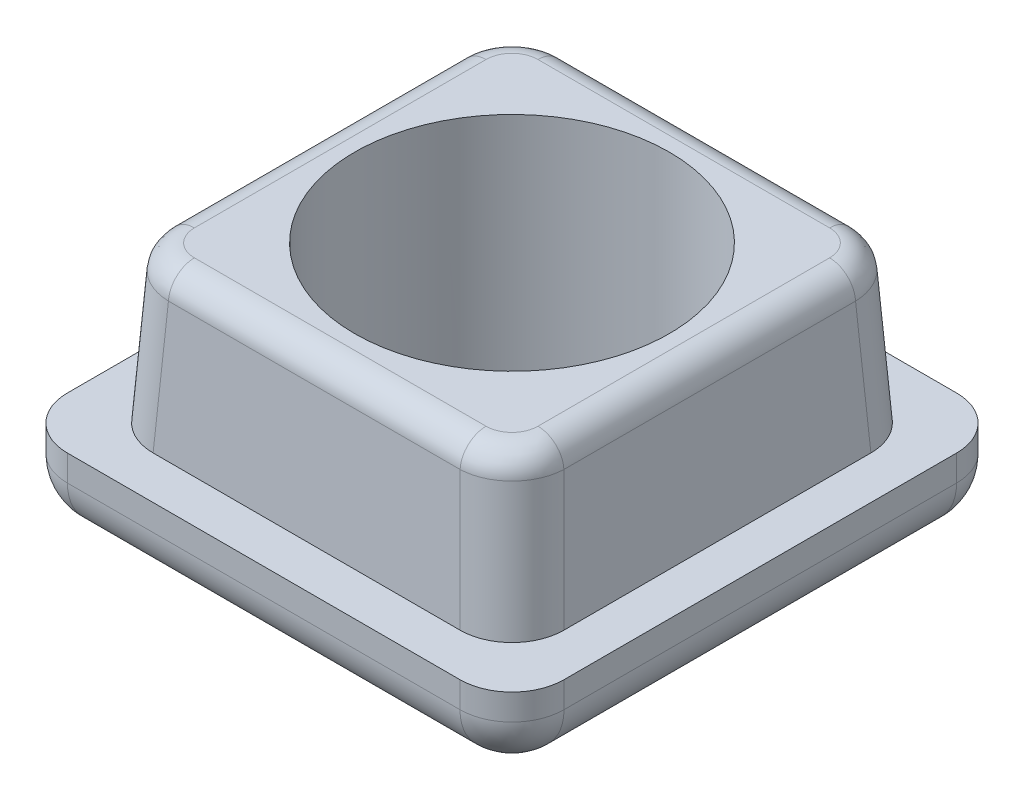
SolidWorks part; units mm, degrees
ref_plane "Front Plane" through (0, 0, 0) normal (0, 0, 1) x (1, 0, 0)
ref_plane "Top Plane" through (0, 0, 0) normal (0, 1, 0) x (1, 0, 0)
ref_plane "Right Plane" through (0, 0, 0) normal (1, 0, 0) x (0, 0, -1)
sketch "Sketch1" plane through (0, 0, 0) normal (0, 1, 0) x (1, 0, 0)
  line L1 (0, 0) -> (19.1, 0)
  line L2 (0, 0) -> (0, 19.1)
  line L3 (0, 19.1) -> (19.1, 19.1)
  line L4 (19.1, 0) -> (19.1, 19.1)
  dimension "D1" = 19.1
extrude "Boss-Extrude1" add sketch "Sketch1" along normal blind 3
sketch "Sketch2" plane through (0, 3, 0) normal (0, 1, 0) x (1, 0, 0)
  line L8 (1.65, 1.65) -> (17.45, 1.65)
  line L9 (17.45, 1.65) -> (17.45, 17.45)
  line L10 (1.65, 17.45) -> (1.65, 1.65)
  line L11 (17.45, 17.45) -> (1.65, 17.45)
  line L12 (1.65, 1.65) -> (17.45, 1.65)
  line L13 (17.45, 1.65) -> (17.45, 17.45)
  line L14 (1.65, 17.45) -> (1.65, 1.65)
  line L15 (17.45, 17.45) -> (1.65, 17.45)
  dimension "D1" = 1.65
ref_plane "Plane1" through (0, 9, 0) normal (0, 1, 0) x (1, 0, 0)
sketch "Sketch3" plane through (0, 9, 0) normal (0, 1, 0) x (1, 0, 0)
  line L8 (2, 2) -> (17.1, 2)
  line L9 (2, 17.1) -> (2, 2)
  line L10 (17.1, 17.1) -> (2, 17.1)
  line L11 (17.1, 2) -> (17.1, 17.1)
  line L12 (2, 2) -> (17.1, 2)
  line L13 (2, 17.1) -> (2, 2)
  line L14 (17.1, 17.1) -> (2, 17.1)
  line L15 (17.1, 2) -> (17.1, 17.1)
  dimension "D1" = 2
loft "Loft1" add profiles "Sketch2", "Sketch3"
sketch "Sketch4" plane through (0, 0, 0) normal (0, -1, 0) x (1, 0, 0)
  line L0 (0, 0) -> (19.1, 0) construction
  line L1 (0, -19.1) -> (0, 0) construction
  circle A0 centre (9.55, -9.55) radius 6.05
  point P4 (9.55, 0)
  point P7 (0, -9.55)
  dimension "D1" = 12.1
extrude "Cut-Extrude1" cut sketch "Sketch4" against normal through all
ref_plane "Plane2" through (9.55, 0, 0) normal (1, 0, 0) x (0, 0, -1)
ref_plane "Plane3" through (0, 0, -9.55) normal (0, 0, 1) x (1, 0, 0)
fillet "Fillet1" radius 2 8 edges at (19.1, 1.5, 0) (0, 1.5, 0) (19.1, 1.5, -19.1) (0, 1.5, -19.1)
fillet "Fillet2" radius 1 8 edges
fillet "Fillet3" radius 2 8 edges at (0.5858, 0, -0.5858) (0, 0, -9.55) (0.5858, 0, -18.5142) (9.55, 0, -19.1) (18.5142, 0, -18.5142) (19.1, 0, -9.55) (18.5142, 0, -0.5858) (9.55, 0, 0)
